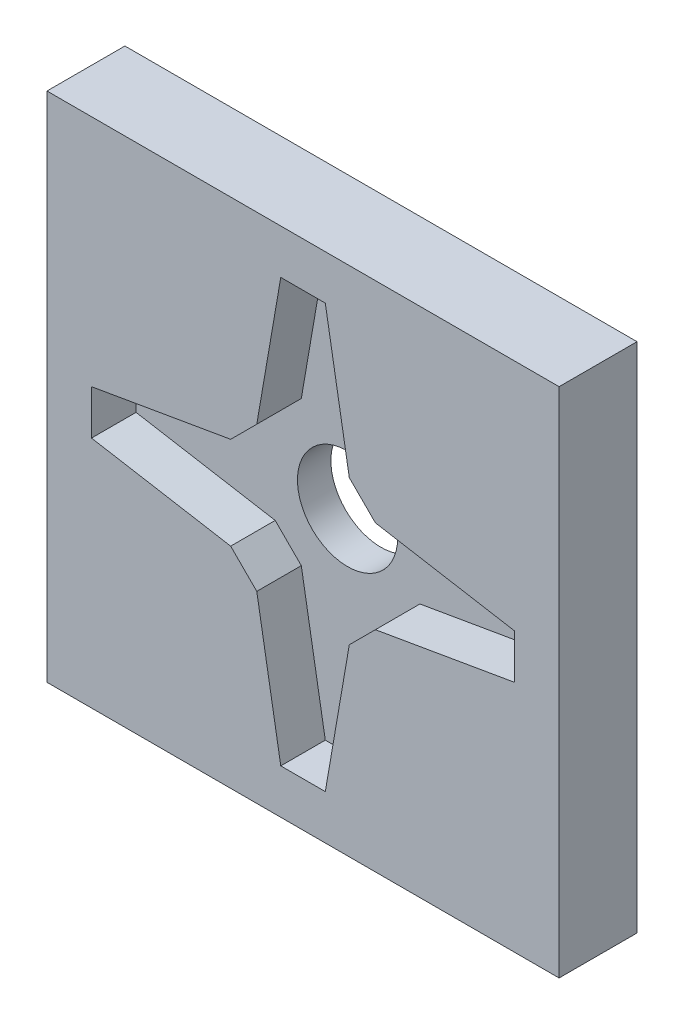
SolidWorks part; units mm, degrees
ref_plane "Front Plane" through (0, 0, 0) normal (0, 0, 1) x (1, 0, 0)
ref_plane "Top Plane" through (0, 0, 0) normal (0, 1, 0) x (1, 0, 0)
ref_plane "Right Plane" through (0, 0, 0) normal (1, 0, 0) x (0, 0, -1)
sketch "Sketch1" plane through (0, 0, 0) normal (0, 0, 1) x (1, 0, 0)
  line L0 (-2, 19) -> (2, 19)
  line L1 (2, 19) -> (4.5, 4.5)
  line L2 (4.5, 4.5) -> (19, 2)
  line L3 (19, 2) -> (19, -2)
  line L4 (0, 27.0151) -> (0, -12.3459) construction
  line L5 (-19, 2) -> (-19, -2)
  line L6 (-4.5, 4.5) -> (-19, 2)
  line L7 (-2, 19) -> (-4.5, 4.5)
  line L8 (-22.7592, 0) -> (31.619, 0) construction
  line L9 (-2, -19) -> (-4.5, -4.5)
  line L10 (-4.5, -4.5) -> (-19, -2)
  line L11 (4.5, -4.5) -> (19, -2)
  line L12 (2, -19) -> (4.5, -4.5)
  line L13 (-2, -19) -> (2, -19)
  line L15 (23, -23) -> (-23, -23)
  line L16 (23, -23) -> (23, 23)
  line L17 (23, 23) -> (-23, 23)
  line L18 (-23, -23) -> (-23, 23)
  line L19 (23, -23) -> (-23, 23) construction
  line L20 (23, 23) -> (-23, -23) construction
  point P12 (0, 19)
  point P14 (0, -19)
  point P18 (-19, 0)
  point P19 (19, 0)
  point P21 (0, 0)
  dimension "D1" = 2
  dimension "D2" = 2
  dimension "D3" = 4.5
  dimension "D4" = 4.5
  dimension "D5" = 19
  dimension "D6" = 19
  dimension "D7" = 0
  dimension "D8" = 0
  dimension "D9" = 4
  dimension "D10" = 4
extrude "Boss-Extrude1" add sketch "Sketch1" along normal blind 7
sketch "Sketch2" plane through (0, 0, 0) normal (0, 0, 1) x (1, 0, 0)
  line L1 (-23, 23) -> (23, 23)
  line L2 (-23, 23) -> (-23, -23)
  line L3 (-23, -23) -> (23, -23)
  line L4 (23, 23) -> (23, -23)
extrude "Boss-Extrude2" add sketch "Sketch2" along normal blind 3
sketch "Sketch3" plane through (0, 0, 0) normal (0, 0, 1) x (1, 0, 0)
  circle A1 centre (0, 0) radius 4.5
  dimension "D1" = 9
extrude "Cut-Extrude1" cut sketch "Sketch3" along normal blind 3
sketch "Sketch4" plane through (0, 0, 7) normal (0, 0, 1) x (1, 0, 0)
  line L0 (-4.1552, 6.5) -> (-6.5, 4.1552)
  line L1 (-2, 19) -> (-4.5, 4.5) construction
  line L2 (-4.5, 4.5) -> (-19, 2) construction
  line L3 (-6.5, 4.1552) -> (-6.5, -4.1552)
  line L4 (-4.1552, 6.5) -> (4.1552, 6.5)
  line L6 (0, 10.6009) -> (0, -6.2676) construction
  line L8 (6.5, 4.1552) -> (6.5, -4.1552)
  line L9 (4.1552, 6.5) -> (6.5, 4.1552)
  line L10 (10.1012, 0) -> (-10.6601, 0) construction
  line L12 (4.1552, -6.5) -> (6.5, -4.1552)
  line L14 (-4.1552, -6.5) -> (4.1552, -6.5)
  line L16 (-4.1552, -6.5) -> (-6.5, -4.1552)
  point P11 (0, 6.5)
  point P15 (0, -6.5)
  point P18 (6.5, 0)
  point P20 (-6.5, 0)
  dimension "D1" = 6.5
  dimension "D2" = 6.5
  dimension "D3" = 0
  dimension "D4" = 0
extrude "Cut-Extrude2" cut sketch "Sketch4" against normal blind 4
